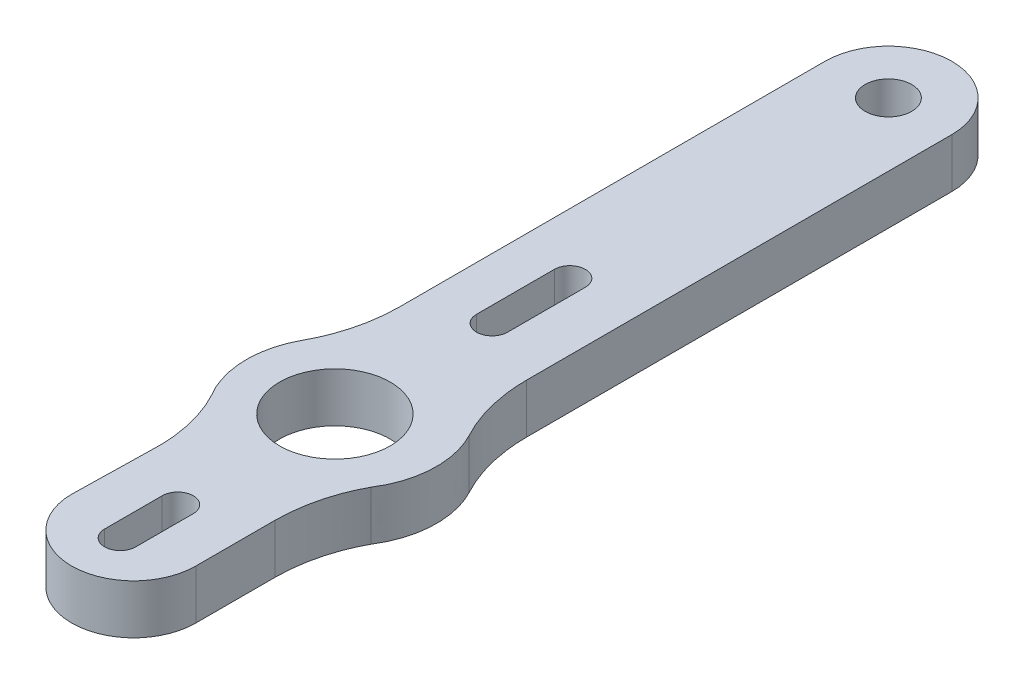
SolidWorks part; units mm, degrees
material "Acrylic (Medium-high impact)"
ref_plane "Front Plane" through (0, 0, 0) normal (0, 0, 1) x (1, 0, 0)
ref_plane "Top Plane" through (0, 0, 0) normal (0, 1, 0) x (1, 0, 0)
ref_plane "Right Plane" through (0, 0, 0) normal (1, 0, 0) x (0, 0, -1)
sketch "Sketch1" plane through (0, 0, 0) normal (0, 1, 0) x (1, 0, 0)
  line L1 (-3.8805, 24.4467) -> (-3.8805, -2.8742)
  line L2 (4.2752, 24.4794) -> (4.2752, -2.8747)
  line L4 (3.994, -18.7597) -> (3.994, -23.8435)
  line L5 (-3.9919, -23.8435) -> (-3.8805, -18.3161)
  line L6 (0.9993, -0.813) -> (0.9993, 4.1872)
  line L7 (-0.9972, 4.1872) -> (-0.9972, -0.813)
  line L8 (0.9993, -24.7137) -> (0.9993, -21.0136)
  line L9 (-0.9972, -24.7137) -> (-0.9972, -21.0136)
  line L11 (-3.9919, -23.8435) -> (3.994, -23.8435) construction
  line L12 (0.001, -7.3632) -> (0.001, -14.4634) construction
  arc A0 (4.2752, 24.4794) -> (-3.8805, 24.4467) centre (0.1973, 24.463) ccw
  arc A1 (3.994, -23.8435) -> (-3.9919, -23.8435) centre (0.0011, -23.8435) cw
  circle A2 centre (0.1973, 24.463) radius 1.4986
  circle A3 centre (0.001, -10.9133) radius 3.556
  arc A4 (-0.9972, -24.7137) -> (0.9993, -24.7137) centre (0.0011, -24.7137) ccw
  arc A5 (-0.9972, -21.0136) -> (0.9993, -21.0136) centre (0.0011, -21.0136) cw
  arc A6 (-0.9972, 4.1872) -> (0.9993, 4.1872) centre (0.0011, 4.1872) cw
  arc A7 (0.9993, -0.813) -> (-0.9972, -0.813) centre (0.0011, -0.813) cw
  spline S2 degree 3 poles (-5.0163, -13.8183) (-6.0956, -12.0231) (-6.1865, -9.7355) (-5.1264, -7.8162) knots 1.005659 1.005659 1.005659 1.005659 2 2 2 2
  spline S3 degree 3 poles (-5.1264, -7.8162) (-4.3086, -6.3339) (-3.8799, -4.5677) (-3.8805, -2.8742) knots 2 2 2 2 3 3 3 3
  spline S7 degree 3 poles (4.2752, -2.8747) (4.2752, -4.5682) (4.7046, -6.3342) (5.5229, -7.8162) knots 8 8 8 8 9 9 9 9
  spline S8 degree 3 poles (5.5229, -7.8162) (6.5299, -9.7664) (6.3739, -12.0533) (5.2418, -13.8183) knots 9 9 9 9 10 10 10 10
  spline S9 degree 3 poles (5.2418, -13.8183) (4.4234, -15.3002) (3.994, -17.0663) (3.994, -18.7597) knots 11 11 11 11 12 12 12 12
  spline S13 degree 3 poles (-3.8805, -18.3161) (-3.8805, -16.7747) (-4.2714, -15.1672) (-5.0163, -13.8183) knots 17 17 17 17 18 18 18 18
  point P53 (0.1973, 24.463)
  dimension "D2" = 2.9972
  dimension "D3" = 7.112
  dimension "D4" = 3.7001
extrude "Boss-Extrude2" add sketch "Sketch1" along normal blind 3.175
